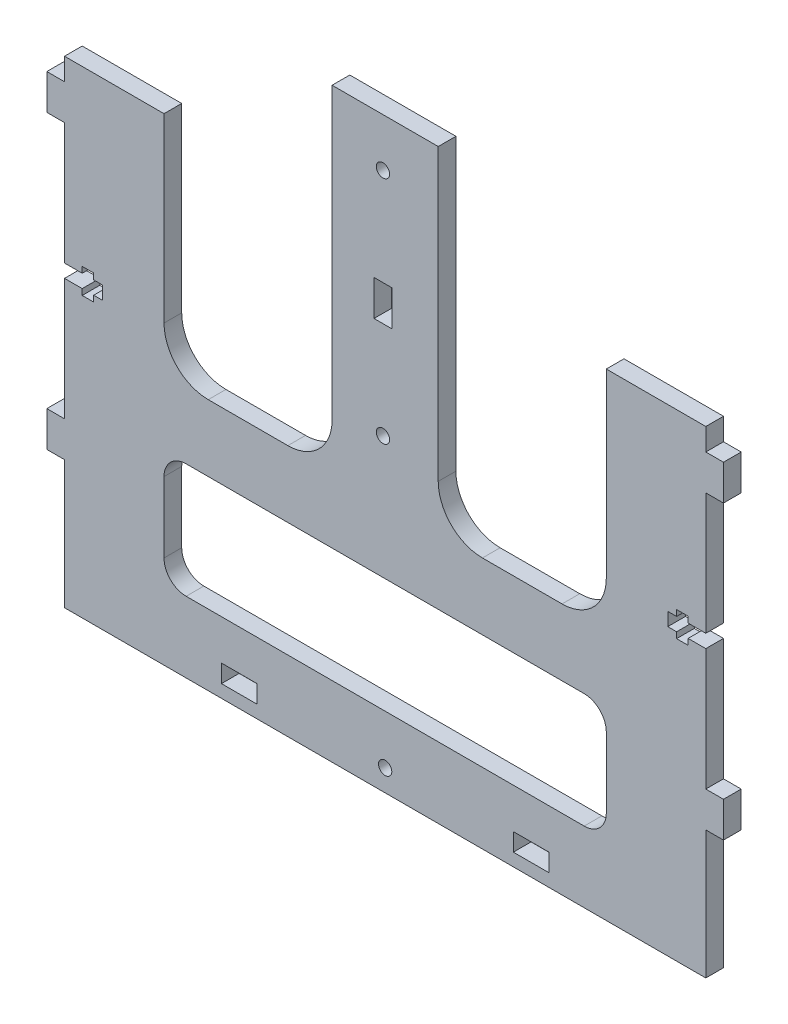
SolidWorks part; units mm, degrees
ref_plane "前视基准面" through (0, 0, 0) normal (0, 0, 1) x (1, 0, 0)
ref_plane "上视基准面" through (0, 0, 0) normal (0, 1, 0) x (1, 0, 0)
ref_plane "右视基准面" through (0, 0, 0) normal (1, 0, 0) x (0, 0, -1)
sketch "草图1" plane through (0, 0, 0) normal (0, 0, 1) x (1, 0, 0)
  line L1 (145, 0) -> (145, 66) construction
  line L9 (145, 64.5) -> (149, 64.5)
  line L10 (149, 64.5) -> (149, 63.15)
  line L11 (149, 63.15) -> (151.6, 63.15)
  line L12 (151.6, 63.15) -> (151.6, 64.5)
  line L13 (151.6, 64.5) -> (153.6, 64.5)
  line L14 (153.6, 64.5) -> (153.6, 67.5)
  line L23 (145, 66) -> (143.6922, 66) construction
  line L24 (145, 64.5) -> (145, 66) construction
  line L25 (151.6, 68.85) -> (151.6, 67.5)
  line L26 (149, 67.5) -> (149, 68.85)
  line L27 (151.6, 67.5) -> (153.6, 67.5)
  line L28 (149, 68.85) -> (151.6, 68.85)
  line L29 (145, 67.5) -> (149, 67.5)
  line L30 (145, 0) -> (145, 29) construction
  line L31 (145, 29) -> (141, 29)
  line L32 (141, 29) -> (141, 37)
  line L33 (141, 37) -> (145, 37)
  line L34 (145, 37) -> (145, 64.5)
  line L35 (141, 33) -> (142.703, 33) construction
  line L36 (145, 103) -> (141, 103)
  line L38 (141, 103) -> (141, 95)
  line L39 (141, 95) -> (145, 95)
  line L40 (145, 95) -> (145, 67.5)
  line L42 (145, 29) -> (145, 0)
  line L43 (294, 33) -> (292.297, 33) construction
  line L44 (290, 64.5) -> (290, 66) construction
  line L45 (290, 66) -> (291.3078, 66) construction
  line L46 (290, 0) -> (290, 66) construction
  line L47 (290, 95) -> (290, 67.5)
  line L48 (294, 95) -> (290, 95)
  line L49 (294, 103) -> (294, 95)
  line L51 (290, 103) -> (294, 103)
  line L52 (290, 37) -> (290, 64.5)
  line L53 (294, 37) -> (290, 37)
  line L54 (294, 29) -> (294, 37)
  line L55 (290, 29) -> (294, 29)
  line L56 (290, 0) -> (290, 29) construction
  line L57 (290, 67.5) -> (286, 67.5)
  line L58 (286, 68.85) -> (283.4, 68.85)
  line L59 (283.4, 67.5) -> (281.4, 67.5)
  line L60 (286, 67.5) -> (286, 68.85)
  line L61 (283.4, 68.85) -> (283.4, 67.5)
  line L62 (281.4, 64.5) -> (281.4, 67.5)
  line L63 (283.4, 64.5) -> (281.4, 64.5)
  line L64 (283.4, 63.15) -> (283.4, 64.5)
  line L65 (286, 63.15) -> (283.4, 63.15)
  line L66 (286, 64.5) -> (286, 63.15)
  line L67 (290, 64.5) -> (286, 64.5)
  line L76 (145, 103) -> (145, 108)
  line L79 (239.5, 57) -> (257.5, 57)
  line L82 (195.5, 57) -> (177.5, 57)
  line L88 (145, 0) -> (290, 0)
  line L89 (290, 0) -> (290, 29)
  line L90 (145, 108) -> (167.5, 108)
  line L91 (167.5, 108) -> (167.5, 67)
  line L92 (180.485, 6.915) -> (180.485, 2.885)
  line L93 (246.485, 6.915) -> (254.515, 6.915)
  line L94 (246.485, 6.915) -> (246.485, 2.885)
  line L95 (246.485, 2.885) -> (254.515, 2.885)
  line L96 (254.515, 6.915) -> (254.515, 2.885)
  line L97 (290, 103) -> (290, 108)
  line L98 (290, 108) -> (267.5, 108)
  line L99 (188.515, 6.915) -> (180.485, 6.915)
  line L100 (188.515, 6.915) -> (188.515, 2.885)
  line L101 (188.515, 2.885) -> (180.485, 2.885)
  line L102 (267.5, 108) -> (267.5, 67)
  line L103 (205.5, 67) -> (205.5, 132.57)
  line L106 (205.5, 132.57) -> (229.5, 132.57)
  line L107 (229.5, 132.57) -> (229.5, 67)
  line L108 (214.98, 99.6743) -> (214.98, 91.6343)
  line L109 (214.98, 91.6343) -> (219.02, 91.6343)
  line L110 (219.02, 91.6343) -> (219.02, 99.6743)
  line L111 (219.02, 99.6743) -> (214.98, 99.6743)
  line L116 (215, 99.6543) -> (215, 91.6543) construction
  line L117 (215, 91.6543) -> (219, 91.6543) construction
  line L118 (217, 99.6743) -> (217, 121.6543) construction
  line L119 (217, 91.6343) -> (217, 69.6543) construction
  line L120 (219, 91.6543) -> (219, 99.6543) construction
  line L121 (172.5, 41.9343) -> (262.5, 41.9343)
  line L122 (167.5, 36.9343) -> (167.5, 21)
  line L123 (172.5, 16) -> (262.5, 16)
  line L124 (267.5, 36.9343) -> (267.5, 21)
  line L125 (219, 99.6543) -> (215, 99.6543) construction
  arc A0 (267.5, 67) -> (257.5, 57) centre (257.5, 67) cw
  arc A1 (239.5, 57) -> (229.5, 67) centre (239.5, 67) cw
  arc A2 (205.5, 67) -> (195.5, 57) centre (195.5, 67) cw
  arc A3 (177.5, 57) -> (167.5, 67) centre (177.5, 67) cw
  circle A4 centre (217.5, 4.9) radius 1.5
  arc A7 (267.5, 36.9343) -> (262.5, 41.9343) centre (262.5, 36.9343) ccw
  arc A8 (267.5, 21) -> (262.5, 16) centre (262.5, 21) cw
  arc A9 (172.5, 16) -> (167.5, 21) centre (172.5, 21) cw
  arc A10 (172.5, 41.9343) -> (167.5, 36.9343) centre (172.5, 36.9343) ccw
  circle A11 centre (217, 121.6543) radius 1.5
  circle A12 centre (217, 69.6543) radius 1.5
  point P15 (144.3461, 66)
  point P73 (229.5, 57.9343)
  point P76 (205.5, 57.9343)
  dimension "D13" = 10
  dimension "D14" = 5
  dimension "D2" = 16
  dimension "D3" = 4
  dimension "D4" = 2
  dimension "D5" = 2.6
  dimension "D6" = 1.35
  dimension "D7" = 0.02
  dimension "D8" = 1.5
  dimension "D9" = 4
  dimension "D10" = 8
  dimension "D11" = 145
extrude "凸台-拉伸1" add sketch "草图1" along normal blind 4 contours L51 L49 L48 L47 L57 L60 L58 L61 L59 L62 L63 L64 L65 L66 L67 L52 L53 L54 L55 L89 L88 L42 L31 L32 L33 L34 L9 L10 L11 L12 L13 L14 L27 L25 L28 L26 L29 L40 L39 L38 L36 A3 L82 A2 A1 L79 A0
sketch "草图2" plane through (290, 0, 0) normal (1, 0, 0) x (0, 0, -1)
  line L0 (-2, 67.5) -> (-2, 64.5)
  line L1 (-4, 67.5) -> (0, 67.5) construction
  line L2 (-4, 64.5) -> (0, 64.5) construction
  circle A0 centre (-2, 66) radius 1.5
